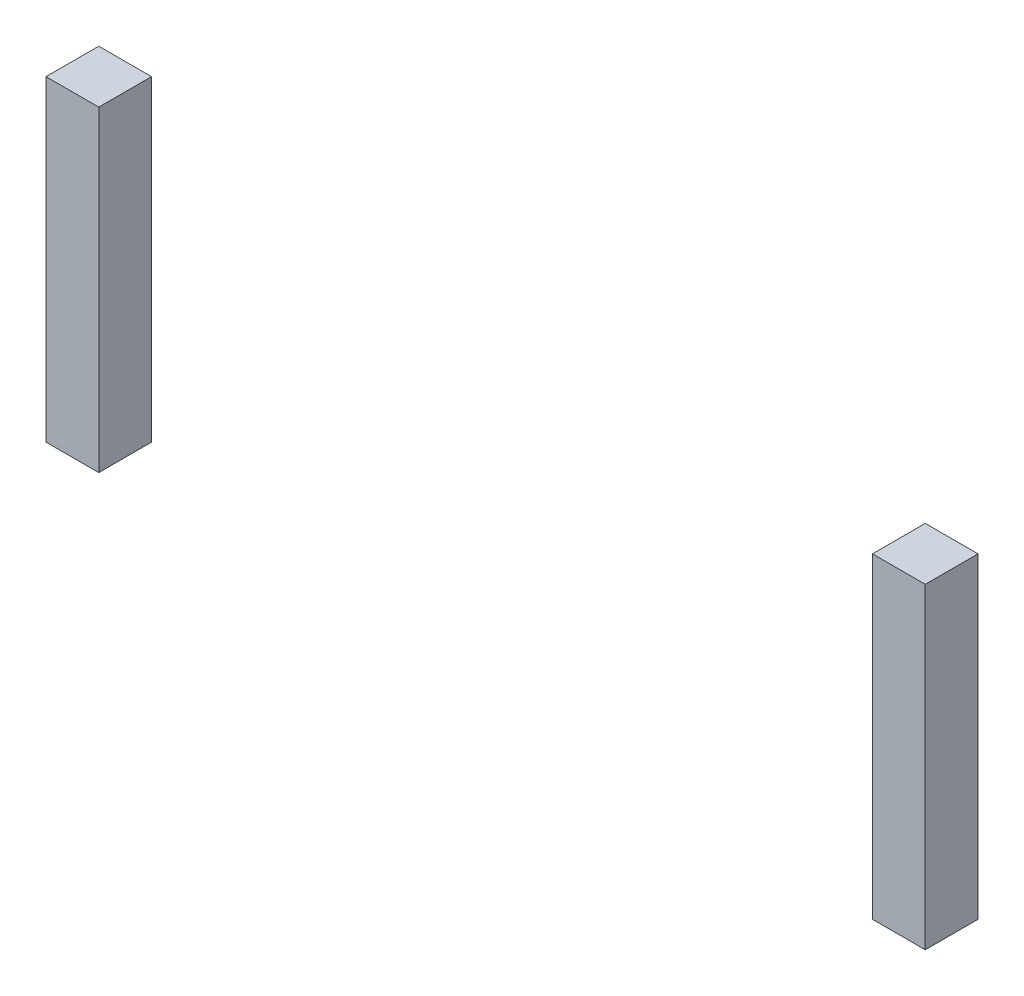
SolidWorks part; units mm, degrees
ref_plane "前视基准面" through (0, 0, 0) normal (0, 0, 1) x (1, 0, 0)
ref_plane "上视基准面" through (0, 0, 0) normal (0, 1, 0) x (1, 0, 0)
ref_plane "右视基准面" through (0, 0, 0) normal (1, 0, 0) x (0, 0, -1)
other "Configuration Table"
sketch "草图1" plane through (0, 0, 0) normal (0, 0, 1) x (1, 0, 0)
  line L1 (-55.7605, 150.0471) -> (-25.7605, 150.0471)
  line L2 (-55.7605, 150.0471) -> (-55.7605, -29.9529)
  line L3 (-55.7605, -29.9529) -> (-25.7605, -29.9529)
  line L4 (-25.7605, 150.0471) -> (-25.7605, -29.9529)
  line L5 (414.2395, 150.0471) -> (444.2395, 150.0471)
  line L6 (414.2395, 150.0471) -> (414.2395, -29.9529)
  line L7 (414.2395, -29.9529) -> (444.2395, -29.9529)
  line L8 (444.2395, 150.0471) -> (444.2395, -29.9529)
  dimension "D1" = 180
  dimension "D2" = 30
  dimension "D3" = 440
extrude "凸台-拉伸1" add sketch "草图1" along normal blind 30 contours L5 L8 L7 L6 | L1 L4 L3 L2
